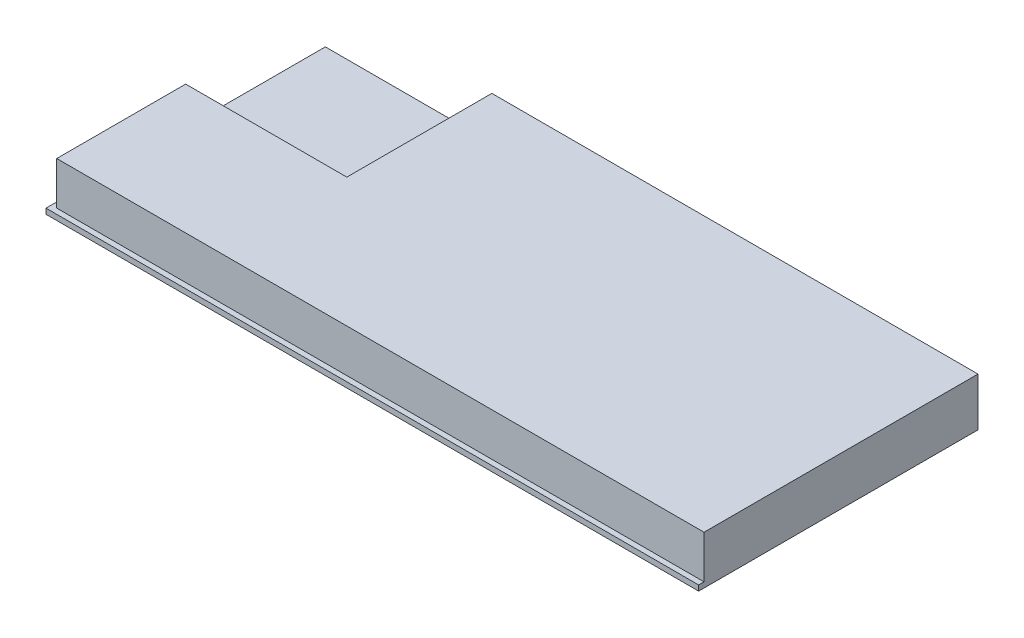
SolidWorks part; units mm, degrees
ref_plane "前视基准面" through (0, 0, 0) normal (0, 0, 1) x (1, 0, 0)
ref_plane "上视基准面" through (0, 0, 0) normal (0, 1, 0) x (1, 0, 0)
ref_plane "右视基准面" through (0, 0, 0) normal (1, 0, 0) x (0, 0, -1)
other "Configuration Table"
sketch "草图1" plane through (0, 0, 0) normal (0, 1, 0) x (1, 0, 0)
  line L1 (-6075, -1300) -> (0, -1300)
  line L2 (-6075, -1300) -> (-6075, 1300)
  line L3 (-6075, 1300) -> (0, 1300)
  line L4 (0, -1300) -> (0, 1300)
  line L5 (-6075, -1300) -> (0, 1300) construction
  line L6 (-6075, 1300) -> (0, -1300) construction
  point P0 (-3037.5, 0)
  dimension "D1" = 2600
  dimension "D2" = 6075
extrude "凸台-拉伸1" add sketch "草图1" along normal blind 50
sketch "草图2" plane through (0, 50, 0) normal (0, 1, 0) x (1, 0, 0)
  line L0 (0, 1300) -> (0, -1250)
  line L1 (0, 1300) -> (-6075, 1300) construction
  line L2 (0, -1250) -> (-6025, -1250)
  line L3 (-6025, -1250) -> (-6025, -50)
  line L4 (-6025, -50) -> (-4525, -50)
  line L5 (-4525, -50) -> (-4525, 1300)
  line L6 (-4525, 1300) -> (0, 1300)
  line L7 (-6075, 1300) -> (-6075, -1300) construction
  line L8 (-6075, -1300) -> (0, -1300) construction
  line L9 (0, -1300) -> (0, 1300) construction
  dimension "D1" = 1550
  dimension "D2" = 1350
  dimension "D3" = 50
  dimension "D4" = 50
extrude "凸台-拉伸2" add sketch "草图2" along normal blind 400
